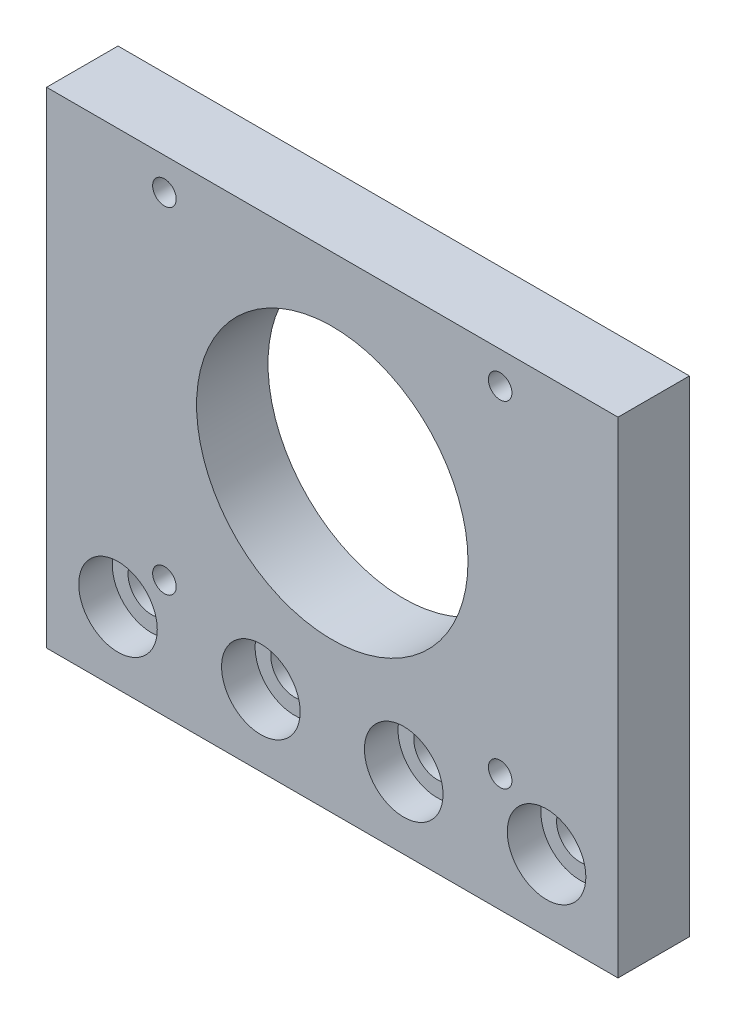
SolidWorks part; units mm, degrees
ref_plane "前视基准面" through (0, 0, 0) normal (0, 0, 1) x (1, 0, 0)
ref_plane "上视基准面" through (0, 0, 0) normal (0, 1, 0) x (1, 0, 0)
ref_plane "右视基准面" through (0, 0, 0) normal (1, 0, 0) x (0, 0, -1)
sketch "草图1" plane through (0, 0, 0) normal (0, 0, 1) x (1, 0, 0)
  line L1 (-40, -40) -> (40, -40)
  line L2 (-40, -40) -> (-40, 28)
  line L3 (-40, 28) -> (40, 28)
  line L4 (40, -40) -> (40, 28)
  point P4 (0, 28)
  dimension "D1" = 40
  dimension "D2" = 80
  dimension "D3" = 68
extrude "凸台-拉伸1" add sketch "草图1" against normal blind 10
sketch "草图2" plane through (0, 0, 0) normal (0, 0, 1) x (1, 0, 0)
  circle A0 centre (0, 0) radius 19
  dimension "D1" = 38
extrude "切除-拉伸1" cut sketch "草图2" against normal blind 10
sketch "草图3" plane through (0, 0, 0) normal (0, 0, 1) x (1, 0, 0)
  line L0 (-40, -40) -> (40, -40) construction
  line L1 (40, -40) -> (40, 28) construction
  line L2 (0, 0) -> (0, -16.4447) construction
  point P0 (30, -30)
  point P9 (-30, -30)
  point P15 (10, -30)
  point P16 (-10, -30)
  point P17 (-30, -30)
  dimension "D1" = 10
  dimension "D2" = 10
  dimension "D3" = 4
hole_wizard "M6 内六角花型圆柱头螺钉的柱形沉头孔1" positions "草图3" profile "草图4" counterbore size "M6" standard "GB" end condition through all
sketch "草图4" plane through (30, -30, 0) normal (1, 0, 0) x (0, -1, 0)
  line L0 (0, 0) -> (0, 10)
  line L1 (0, 10) -> (3.3, 10)
  line L3 (3.3, 10) -> (3.3, 4.7)
  line L4 (3.3, 4.7) -> (5.5, 4.7)
  line L5 (5.5, 4.7) -> (5.5, 0)
  line L7 (5.5, 0) -> (0, 0)
  line L11 (0, -6.35) -> (0, 107.95) construction
  dimension "通孔孔直径" = 6.6
  dimension "通孔孔深度" = 10
  dimension "柱形沉头孔直径" = 11
  dimension "柱形沉头孔深度" = 4.7
sketch "草图5" plane through (0, 0, 0) normal (0, 0, 1) x (1, 0, 0)
  line L1 (-23.5, -23.5) -> (23.5, -23.5) construction
  line L2 (-23.5, -23.5) -> (-23.5, 23.5) construction
  line L3 (-23.5, 23.5) -> (23.5, 23.5) construction
  line L4 (23.5, -23.5) -> (23.5, 23.5) construction
  line L5 (-23.5, -23.5) -> (23.5, 23.5) construction
  line L6 (-23.5, 23.5) -> (23.5, -23.5) construction
  point P0 (0, 0)
  point P1 (23.5, 23.5)
  point P2 (-23.5, -23.5)
  point P3 (-23.5, 23.5)
  point P4 (23.5, -23.5)
  dimension "D1" = 47
hole_wizard "M4 螺纹孔1" positions "草图5" profile "草图6" tap size "M4" standard "GB" end condition through all
sketch "草图6" plane through (23.5, -23.5, 0) normal (1, 0, 0) x (0, -1, 0)
  line L0 (0, 0) -> (0, 10)
  line L1 (0, 10) -> (1.65, 10)
  line L2 (1.65, 10) -> (1.65, 0)
  line L5 (1.65, 0) -> (0, 0)
  line L11 (0, -6.35) -> (0, 107.95) construction
  dimension "通孔螺纹孔钻头直径" = 3.3
  dimension "通孔螺纹孔钻头深度" = 10
cosmetic thread "孔螺纹线1" parameters "D2"=4
cosmetic thread "孔螺纹线2" parameters "D2"=4
cosmetic thread "孔螺纹线3" parameters "D2"=4
cosmetic thread "孔螺纹线4" parameters "D2"=4
sketch "草图7" plane through (0, 0, -10) normal (0, 0, 1) x (1, 0, 0)
  line L0 (40, -40) -> (40, 28) construction
  circle A0 centre (30, 0) radius 5
  dimension "D1" = 10
  dimension "D2" = 10
extrude "切除-拉伸2" cut sketch "草图7" along normal blind 5
mirror "镜向1" about plane through (0, 0, 0) normal (1, 0, 0) of "切除-拉伸2"
